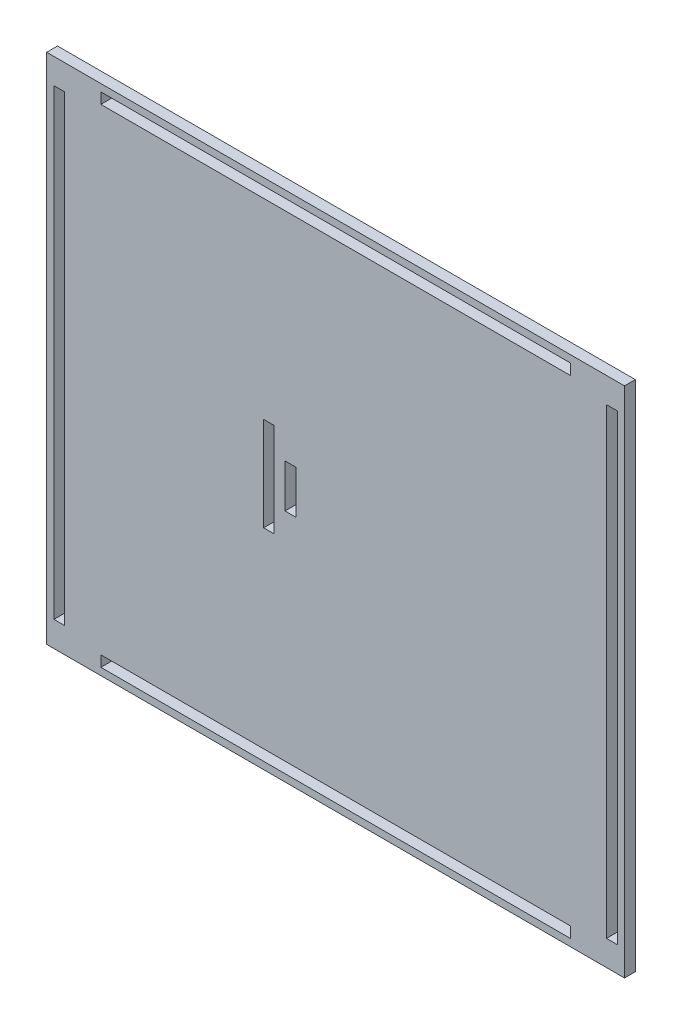
SolidWorks part; units mm, degrees
ref_plane "Front Plane" through (0, 0, 0) normal (0, 0, 1) x (1, 0, 0)
ref_plane "Top Plane" through (0, 0, 0) normal (0, 1, 0) x (1, 0, 0)
ref_plane "Right Plane" through (0, 0, 0) normal (1, 0, 0) x (0, 0, -1)
sketch "Sketch1" plane through (0, 0, 0) normal (0, 0, 1) x (1, 0, 0)
  line L1 (-78.2255, 39.1132) -> (81.7745, 39.1132)
  line L2 (-78.2255, 39.1132) -> (-78.2255, -102.8868)
  line L3 (-78.2255, -102.8868) -> (81.7745, -102.8868)
  line L4 (81.7745, 39.1132) -> (81.7745, -102.8868)
  line L5 (-63.2255, 37.1132) -> (66.7745, 37.1132)
  line L6 (-63.2255, 37.1132) -> (-63.2255, 34.1132)
  line L7 (-63.2255, 34.1132) -> (66.7745, 34.1132)
  line L8 (66.7745, 37.1132) -> (66.7745, 34.1132)
  line L13 (-63.2255, -97.8868) -> (66.7745, -97.8868)
  line L14 (66.7745, -100.8868) -> (66.7745, -97.8868)
  line L15 (-63.2255, -100.8868) -> (66.7745, -100.8868)
  line L16 (-63.2255, -100.8868) -> (-63.2255, -97.8868)
  line L17 (-76.2255, 32.1132) -> (-73.2255, 32.1132)
  line L18 (-76.2255, 32.1132) -> (-76.2255, -95.8868)
  line L19 (-76.2255, -95.8868) -> (-73.2255, -95.8868)
  line L20 (-73.2255, 32.1132) -> (-73.2255, -95.8868)
  line L21 (79.7745, -95.8868) -> (76.7745, -95.8868)
  line L22 (76.7745, 32.1132) -> (76.7745, -95.8868)
  line L23 (79.7745, 32.1132) -> (76.7745, 32.1132)
  line L24 (79.7745, 32.1132) -> (79.7745, -95.8868)
  line L25 (-18.1451, -18.8868) -> (-15.2255, -18.8868)
  line L26 (-12.2255, -25.8868) -> (-9.2255, -25.8868)
  line L27 (-12.2255, -25.8868) -> (-12.2255, -37.8868)
  line L28 (-12.2255, -37.8868) -> (-9.2255, -37.8868)
  line L29 (-9.2255, -25.8868) -> (-9.2255, -37.8868)
  line L30 (-18.1451, -18.8868) -> (-18.1451, -44.8868)
  line L31 (-18.1451, -44.8868) -> (-15.2255, -44.8868)
  line L32 (-15.2255, -18.8868) -> (-15.2255, -44.8868)
  point P11 (-78.2255, -28.8838)
  point P18 (-10.7255, -37.8868)
  point P20 (-1.3048, 39.1132)
  dimension "D1" = 160
  dimension "D2" = 142
  dimension "D3" = 130
  dimension "D4" = 3
  dimension "D5" = 15
  dimension "D6" = 2
  dimension "D7" = 15
  dimension "D8" = 3
  dimension "D9" = 128
  dimension "D10" = 7
  dimension "D11" = 2
  dimension "D12" = 3
  dimension "D13" = 12
  dimension "D14" = 51
  dimension "D15" = 15
  dimension "D16" = 58
  dimension "D17" = 58
  dimension "D18" = 2
  dimension "D19" = 3
  dimension "D20" = 130
  dimension "D21" = 2
  dimension "D22" = 26
  dimension "D23" = 7
  dimension "D24" = 3
extrude "Boss-Extrude1" add sketch "Sketch1" along normal blind 3
